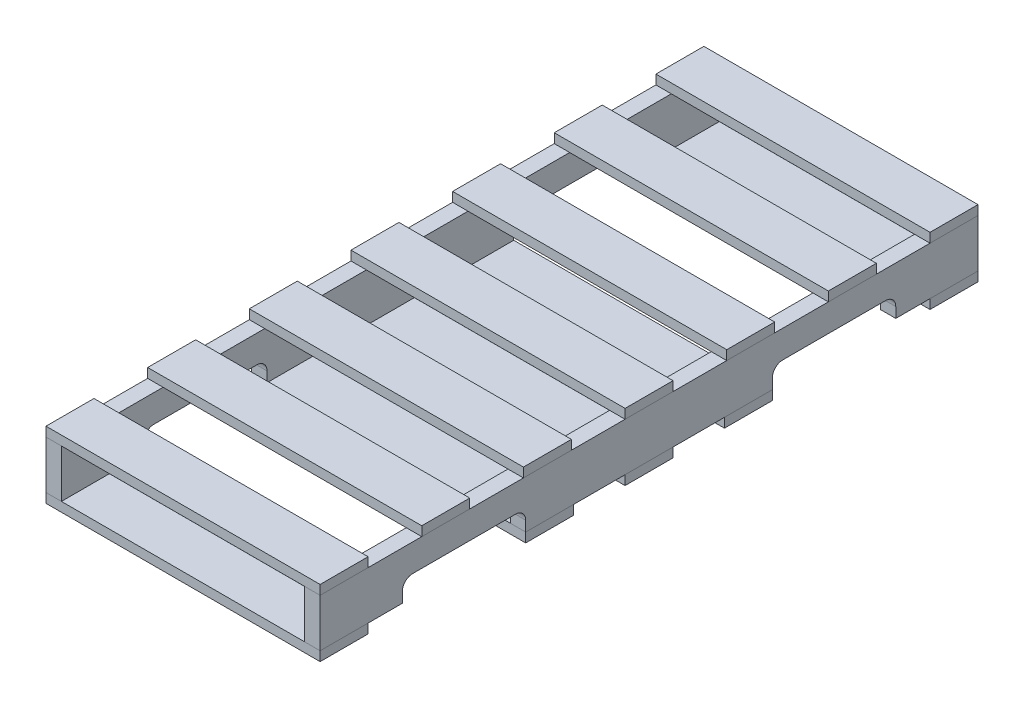
SolidWorks part; units mm, degrees
ref_plane "Front Plane" through (0, 0, 0) normal (0, 0, 1) x (1, 0, 0)
ref_plane "Top Plane" through (0, 0, 0) normal (0, 1, 0) x (1, 0, 0)
ref_plane "Right Plane" through (0, 0, 0) normal (1, 0, 0) x (0, 0, -1)
sketch "Sketch1" plane through (0, 0, 0) normal (0, 0, 1) x (1, 0, 0)
  line L0 (-254, 0) -> (254, 0) construction
  line L5 (-254, 61.976) -> (-254, -61.976) construction
  line L6 (254, 61.976) -> (254, -61.976) construction
  line L11 (-254, -61.976) -> (254, -61.976) construction
  line L12 (-254, 61.976) -> (254, 61.976) construction
  line L13 (-225.425, 61.976) -> (-225.425, -61.976) construction
  line L15 (225.425, 61.976) -> (225.425, -61.976) construction
  line L16 (-225.425, -61.976) -> (-225.425, 61.976) construction
  line L17 (0, 61.976) -> (0, -61.976) construction
  line L18 (-254, 0) -> (-225.425, 0)
  line L19 (225.425, 0) -> (0, 0)
  line L20 (0, 0) -> (-225.425, 0)
  line L22 (-254, 44.5008) -> (254, 44.5008) construction
  line L23 (-254, -44.5008) -> (254, -44.5008) construction
  point P3 (0, 0)
  point P6 (-254, 0)
  point P9 (254, 0)
  point P23 (0, 0)
  dimension "D1" = 28.575
  dimension "Width" = 508
  dimension "Height" = 123.952
  dimension "Maximum Fork Width" = 450.85
  dimension "D3" = 17.4752
  dimension "Maximum Fork Height" = 89.0016
sketch "Sketch2" plane through (0, 0, 0) normal (1, 0, 0) x (0, 0, -1)
  line L0 (609.6, 0) -> (-609.6, 0) construction
  point P4 (0, 0)
  dimension "Depth" = 1219.2
sketch "Sketch3" plane through (0, 0, 0) normal (0, 0, 1) x (1, 0, 0)
  line L5 (-254, -44.5008) -> (254, -44.5008) construction
  line L7 (-254, 44.5008) -> (-225.425, 44.5008)
  line L8 (-254, 44.5008) -> (-254, -44.5008)
  line L9 (-254, -44.5008) -> (-225.425, -44.5008)
  line L10 (-225.425, 44.5008) -> (-225.425, -44.5008)
  line L11 (-254, 44.5008) -> (254, 44.5008) construction
  line L12 (-225.425, -61.976) -> (-225.425, 61.976) construction
  line L14 (225.425, 44.5008) -> (254, 44.5008)
  line L15 (225.425, 44.5008) -> (225.425, -44.5008)
  line L16 (225.425, -44.5008) -> (254, -44.5008)
  line L17 (254, 44.5008) -> (254, -44.5008)
  line L18 (-254, 61.976) -> (-254, -61.976) construction
  line L19 (225.425, 61.976) -> (225.425, -61.976) construction
extrude "Boss-Extrude1" add sketch "Sketch3" along normal up to vertex (609.6 mm away) and the other way up to vertex (609.6 mm away) up to point (0, 0, 609.6) other way up to point (0, 0, -609.6)
sketch "Sketch4" plane through (0, 44.5008, 0) normal (0, 1, 0) x (1, 0, 0)
  line L0 (254, -609.6) -> (254, 609.6) construction
  line L1 (-254, -609.6) -> (254, -609.6)
  line L2 (-254, -609.6) -> (-254, -520.7)
  line L3 (-254, -520.7) -> (254, -520.7)
  line L4 (254, -609.6) -> (254, -520.7)
  line L5 (-254, -421.2167) -> (254, -421.2167)
  line L6 (-254, -421.2167) -> (-254, -332.3167)
  line L7 (-254, -332.3167) -> (254, -332.3167)
  line L8 (254, -421.2167) -> (254, -332.3167)
  line L9 (-254, -232.8333) -> (254, -232.8333)
  line L10 (-254, -232.8333) -> (-254, -143.9333)
  line L11 (-254, -143.9333) -> (254, -143.9333)
  line L12 (254, -232.8333) -> (254, -143.9333)
  line L13 (-254, -44.45) -> (254, -44.45)
  line L14 (-254, -44.45) -> (-254, 44.45)
  line L15 (-254, 44.45) -> (254, 44.45)
  line L16 (254, -44.45) -> (254, 44.45)
  line L17 (-254, 143.9333) -> (254, 143.9333)
  line L18 (-254, 143.9333) -> (-254, 232.8333)
  line L19 (-254, 232.8333) -> (254, 232.8333)
  line L20 (254, 143.9333) -> (254, 232.8333)
  line L21 (-254, 332.3167) -> (254, 332.3167)
  line L22 (-254, -609.6) -> (-254, 609.6) construction
  line L23 (-254, 332.3167) -> (-254, 421.2167)
  line L24 (-254, 421.2167) -> (254, 421.2167)
  line L25 (254, 332.3167) -> (254, 421.2167)
  line L26 (-254, 520.7) -> (254, 520.7)
  line L27 (-254, 520.7) -> (-254, 609.6)
  line L28 (-254, 609.6) -> (254, 609.6)
  line L29 (254, 520.7) -> (254, 609.6)
  dimension "D1" = 88.9
  dimension "D3" = 99.4833
  dimension "Top Boards" = 7
extrude "Boss-Extrude2" add sketch "Sketch4" along normal up to vertex (17.4752 mm away) separate body up to point (-254, 61.976, 0)
sketch "Sketch5" plane through (0, -44.5008, 0) normal (0, -1, 0) x (1, 0, 0)
  line L0 (254, 609.6) -> (254, -609.6) construction
  line L1 (-254, 609.6) -> (254, 609.6)
  line L2 (-254, 609.6) -> (-254, 520.7)
  line L3 (-254, 520.7) -> (254, 520.7)
  line L4 (254, 609.6) -> (254, 520.7)
  line L5 (-254, -609.6) -> (254, -609.6)
  line L6 (-254, -609.6) -> (-254, -520.7)
  line L7 (-254, -520.7) -> (254, -520.7)
  line L8 (254, -609.6) -> (254, -520.7)
  line L9 (-254, -44.45) -> (254, -44.45)
  line L10 (-254, -44.45) -> (-254, 44.45)
  line L11 (-254, 44.45) -> (254, 44.45)
  line L12 (254, -44.45) -> (254, 44.45)
  line L13 (-254, -44.45) -> (254, 44.45) construction
  line L14 (-254, 44.45) -> (254, -44.45) construction
  line L16 (-254, 609.6) -> (-254, 520.7) construction
  line L17 (254, 609.6) -> (254, 520.7) construction
  line L18 (-254, 228.6) -> (254, 228.6)
  line L19 (-254, 228.6) -> (-254, 139.7)
  line L20 (-254, 139.7) -> (254, 139.7)
  line L21 (254, 228.6) -> (254, 139.7)
  line L22 (-254, -228.6) -> (254, -228.6)
  line L23 (-254, -228.6) -> (-254, -139.7)
  line L24 (-254, -139.7) -> (254, -139.7)
  line L25 (254, -228.6) -> (254, -139.7)
  point P12 (0, 0)
  dimension "D1" = 292.1
  dimension "D2" = 292.1
extrude "Boss-Extrude3" add sketch "Sketch5" along normal up to vertex (17.4752 mm away) separate body up to point (-254, -61.976, 0)
sketch "Sketch8" plane through (254, 0, 0) normal (1, 0, 0) x (0, 0, -1)
  line L1 (-228.6, -44.5008) -> (-457.2, -44.5008)
  line L2 (-228.6, -44.5008) -> (-228.6, -25.4508)
  line L3 (-247.65, -6.4008) -> (-438.15, -6.4008)
  line L4 (-457.2, -44.5008) -> (-457.2, -25.4508)
  line L5 (228.6, -44.5008) -> (457.2, -44.5008)
  line L6 (228.6, -44.5008) -> (228.6, -25.4508)
  line L7 (247.65, -6.4008) -> (438.15, -6.4008)
  line L8 (457.2, -44.5008) -> (457.2, -25.4508)
  arc A0 (438.15, -6.4008) -> (457.2, -25.4508) centre (438.15, -25.4508) cw
  arc A1 (228.6, -25.4508) -> (247.65, -6.4008) centre (247.65, -25.4508) cw
  arc A2 (-228.6, -25.4508) -> (-247.65, -6.4008) centre (-247.65, -25.4508) ccw
  arc A3 (-438.15, -6.4008) -> (-457.2, -25.4508) centre (-438.15, -25.4508) ccw
  point P18 (-457.2, -6.4008)
  dimension "D3" = 19.05
  dimension "D1" = 38.1
  dimension "D2" = 228.6
extrude "Cut-Extrude2" cut sketch "Sketch8" against normal through all both and the other way through all
sketch "Sketch7" plane through (0, 0, 0) normal (0, 1, 0) x (1, 0, 0)
  line L0 (0, 609.6) -> (254, 609.6) construction
  line L2 (254, 609.6) -> (254, 0) construction
  line L3 (254, 0) -> (254, -609.6) construction
  line L4 (254, -609.6) -> (0, -609.6) construction
  line L5 (-254, -609.6) -> (254, -609.6) construction
  line L6 (-254, 609.6) -> (0, 609.6) construction
equation "\"D3@Sketch4\" =  ( \"Depth@Sketch2\" -  ( 3.5 * \"Top Boards@Sketch4\" )  )  /  ( \"Top Boards@Sketch4\" - 1 ) "
